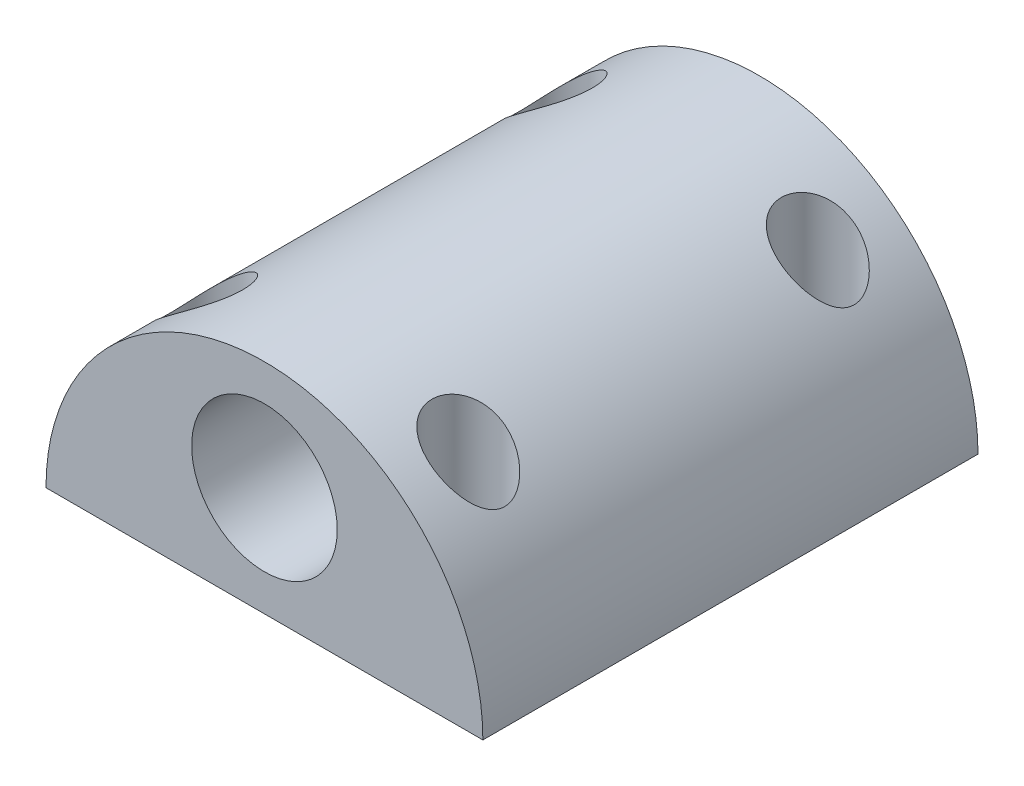
SolidWorks part; units mm, degrees
ref_plane "Front" through (0, 0, 0) normal (0, 0, 1) x (1, 0, 0)
ref_plane "Top" through (0, 0, 0) normal (0, 1, 0) x (1, 0, 0)
ref_plane "Right" through (0, 0, 0) normal (1, 0, 0) x (0, 0, -1)
sketch "Esquisse1" plane through (0, 0, 0) normal (0, 0, 1) x (1, 0, 0)
  line L0 (0, 0) -> (30, 0)
  arc A0 (30, 0) -> (0, 0) centre (15, 0) ccw
  circle A1 centre (15, 7.5) radius 5
  dimension "D2" = 10
  dimension "D3" = 7.5
  dimension "D4" = 15
  dimension "D1" = 30
extrude "Boss.-Extru.1" add sketch "Esquisse1" along normal blind 34
sketch "Esquisse2" plane through (0, 0, 0) normal (0, -1, 0) x (1, 0, 0)
  line L0 (15, 34) -> (15, 0) construction
  line L1 (0, 34) -> (30, 34) construction
  line L2 (0, 0) -> (30, 0) construction
  line L3 (30, 17) -> (0, 17) construction
  line L4 (30, 34) -> (30, 0) construction
  line L5 (0, 34) -> (0, 0) construction
  circle A0 centre (24, 29) radius 1.5
  circle A1 centre (24, 5) radius 1.5
  circle A2 centre (6, 5) radius 1.5
  circle A3 centre (6, 29) radius 1.5
  dimension "D1" = 5
  dimension "D2" = 6
  dimension "D3" = 3
extrude "Enlèv. mat.-Extru.1" cut sketch "Esquisse2" against normal through all
sketch "Esquisse4" plane through (0, 0, 0) normal (0, -1, 0) x (1, 0, 0)
  circle A0 centre (24, 29) radius 2.5
  dimension "D1" = 5
extrude "Enlèv. mat.-Extru.2" cut sketch "Esquisse4" against normal through all from offset 5 offset against normal yes
ref_plane "Plan1" through (15, 0, 0) normal (1, 0, 0) x (0, 0, -1)
mirror "Symétrie1" about plane through (15, 0, 0) normal (1, 0, 0) of "Enlèv. mat.-Extru.2"
ref_plane "Plan2" through (0, 0, 17) normal (0, 0, 1) x (1, 0, 0)
mirror "Symétrie2" about plane through (0, 0, 17) normal (0, 0, 1) of "Symétrie1", "Enlèv. mat.-Extru.2"
